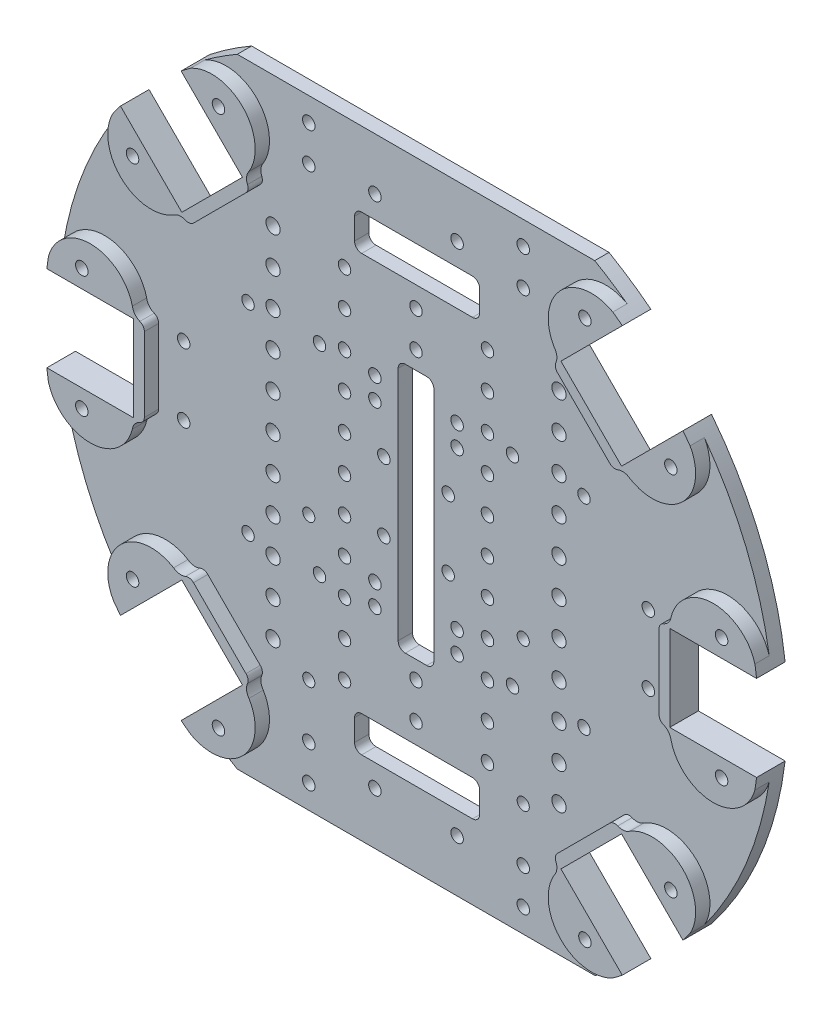
SolidWorks part; units mm, degrees
ref_plane "Front Plane" through (0, 0, 0) normal (0, 0, 1) x (1, 0, 0)
ref_plane "Top Plane" through (0, 0, 0) normal (0, 1, 0) x (1, 0, 0)
ref_plane "Right Plane" through (0, 0, 0) normal (1, 0, 0) x (0, 0, -1)
sketch "Sketch1" plane through (0, 0, 0) normal (0, 0, 1) x (1, 0, 0)
  line L0 (0, 0) -> (0, 100) construction
  line L5 (44.5477, 61.5183) -> (61.7144, 78.685)
  line L6 (44.5477, 61.5183) -> (61.5183, 44.5477)
  line L7 (-12, 75) -> (12, 75) construction
  line L8 (-12, 75) -> (-12, 99.2774) construction
  line L9 (12, 75) -> (12, 99.2774) construction
  line L10 (-17, 89.5) -> (17, 89.5) construction
  line L11 (61.5183, 44.5477) -> (78.685, 61.7144)
  line L12 (75, 12) -> (99.2774, 12)
  line L13 (75, 12) -> (75, -12)
  line L14 (75, -12) -> (99.2774, -12)
  line L15 (61.5183, -44.5477) -> (78.685, -61.7144)
  line L16 (61.5183, -44.5477) -> (44.5477, -61.5183)
  line L17 (44.5477, -61.5183) -> (61.7144, -78.685)
  line L18 (12, -75) -> (12, -99.2774) construction
  line L19 (12, -75) -> (-12, -75) construction
  line L20 (-12, -75) -> (-12, -99.2774) construction
  line L21 (-44.5477, -61.5183) -> (-61.7144, -78.685)
  line L22 (-44.5477, -61.5183) -> (-61.5183, -44.5477)
  line L23 (-61.5183, -44.5477) -> (-78.685, -61.7144)
  line L24 (-75, -12) -> (-99.2774, -12)
  line L25 (-75, -12) -> (-75, 12)
  line L26 (-75, 12) -> (-99.2774, 12)
  line L27 (-61.5183, 44.5477) -> (-78.685, 61.7144)
  line L28 (-61.5183, 44.5477) -> (-44.5477, 61.5183)
  line L29 (-44.5477, 61.5183) -> (-61.7144, 78.685)
  circle A1 centre (0, 0) radius 100
  circle A2 centre (-17, 89.5) radius 1.75 construction
  circle A3 centre (17, 89.5) radius 1.75 construction
  circle A4 centre (51.2652, 75.3069) radius 1.75
  circle A5 centre (75.3069, 51.2652) radius 1.75
  circle A6 centre (89.5, 17) radius 1.75
  circle A7 centre (89.5, -17) radius 1.75
  circle A8 centre (75.3069, -51.2652) radius 1.75
  circle A9 centre (51.2652, -75.3069) radius 1.75
  circle A10 centre (17, -89.5) radius 1.75 construction
  circle A11 centre (-17, -89.5) radius 1.75 construction
  circle A12 centre (-51.2652, -75.3069) radius 1.75
  circle A13 centre (-75.3069, -51.2652) radius 1.75
  circle A14 centre (-89.5, -17) radius 1.75
  circle A15 centre (-89.5, 17) radius 1.75
  circle A16 centre (-75.3069, 51.2652) radius 1.75
  circle A17 centre (-51.2652, 75.3069) radius 1.75
  point P2 (0, 89.5)
  point P4 (0, 75)
  point P12 (0, 75)
  point P19 (0, 89.5)
  dimension "150" = 200
  dimension "D7" = 3.5
  dimension "D2" = 25
  dimension "D3" = 8
  dimension "D4" = 24
  dimension "D5" = 14.5
  dimension "D6" = 34
extrude "Boss-Extrude1" add sketch "Sketch1" along normal blind 4 contours L12 A1 L11 L6 L5 L29 L28 L27 L26 L25 L24 L23 L22 L21 L17 L16 L15 L14 L13 A15 A14 A9 A8 A5 A4 A6 A7 A12 A13 A16 A17
sketch "Sketch2" plane through (0, 0, 4) normal (0, 0, 1) x (1, 0, 0)
  line L0 (0, 35) -> (0, -35) construction
  line L1 (-35, 35) -> (35, 35) construction
  line L2 (-35, 35) -> (-35, -35) construction
  line L3 (-35, -35) -> (35, -35) construction
  line L4 (35, 35) -> (35, -35) construction
  line L5 (-35, 35) -> (35, -35) construction
  line L6 (-35, -35) -> (35, 35) construction
  line L7 (0, 35) -> (0, 80)
  line L8 (-30, -15) -> (30, -15) construction
  line L9 (-30, -15) -> (-30, -55) construction
  line L10 (-30, -55) -> (30, -55) construction
  line L11 (30, -15) -> (30, -55) construction
  line L12 (-30, -15) -> (30, -55) construction
  line L13 (-30, -55) -> (30, -15) construction
  line L14 (-30, 80) -> (30, 80)
  line L15 (0, -55) -> (0, -80)
  line L16 (30, -80) -> (-30, -80)
  line L17 (0, 0) -> (-40, 0) construction
  line L18 (0, 0) -> (40, 0) construction
  line L19 (0, 10) -> (-40, 10)
  line L20 (0, 10) -> (40, 10)
  line L21 (0, 20) -> (-40, 20)
  line L22 (0, 20) -> (40, 20)
  line L23 (0, 30) -> (-40, 30)
  line L24 (0, 30) -> (40, 30)
  line L25 (0, 40) -> (-40, 40)
  line L26 (0, 40) -> (40, 40)
  line L27 (0, 50) -> (-40, 50)
  line L28 (0, 50) -> (40, 50)
  line L29 (0, -10) -> (40, -10)
  line L30 (0, -10) -> (-40, -10)
  line L31 (0, -20) -> (40, -20)
  line L32 (0, -20) -> (-40, -20)
  line L33 (0, -30) -> (40, -30)
  line L34 (0, -30) -> (-40, -30)
  line L35 (0, -40) -> (40, -40)
  line L36 (0, -40) -> (-40, -40)
  line L37 (0, -50) -> (40, -50)
  line L38 (0, -50) -> (-40, -50)
  line L39 (30, -70) -> (-30, -70)
  line L40 (-30, 70) -> (30, 70)
  circle A0 centre (0, 0) radius 100
  circle A1 centre (-30, -55) radius 1.7
  circle A2 centre (-30, -15) radius 1.7
  circle A3 centre (30, -55) radius 1.7
  circle A4 centre (30, -15) radius 1.7
  circle A5 centre (-30, 80) radius 1.75
  circle A6 centre (30, 80) radius 1.75
  circle A7 centre (-30, -80) radius 1.75
  circle A8 centre (30, -80) radius 1.75
  circle A9 centre (-40, 0) radius 2
  circle A10 centre (-20, 0) radius 1.75
  circle A11 centre (0, 0) radius 1.75
  circle A12 centre (40, 0) radius 2
  circle A13 centre (20, 0) radius 1.75
  circle A14 centre (20, 10) radius 1.75
  circle A15 centre (40, 10) radius 2
  circle A16 centre (-20, 10) radius 1.75
  circle A17 centre (-40, 10) radius 2
  circle A18 centre (0, 10) radius 1.75
  circle A19 centre (20, 20) radius 1.75
  circle A20 centre (40, 20) radius 2
  circle A21 centre (-20, 20) radius 1.75
  circle A22 centre (-40, 20) radius 2
  circle A23 centre (0, 20) radius 1.75
  circle A24 centre (20, 30) radius 1.75
  circle A25 centre (40, 30) radius 2
  circle A26 centre (-20, 30) radius 1.75
  circle A27 centre (-40, 30) radius 2
  circle A28 centre (0, 30) radius 1.75
  circle A29 centre (20, 40) radius 1.75
  circle A30 centre (40, 40) radius 2
  circle A31 centre (-20, 40) radius 1.75
  circle A32 centre (-40, 40) radius 2
  circle A33 centre (0, 40) radius 1.75
  circle A34 centre (20, 50) radius 1.75
  circle A35 centre (40, 50) radius 2
  circle A36 centre (-20, 50) radius 1.75
  circle A37 centre (-40, 50) radius 2
  circle A38 centre (0, 50) radius 1.75
  circle A39 centre (40, -10) radius 2
  circle A40 centre (0, -10) radius 1.75
  circle A41 centre (20, -10) radius 1.75
  circle A42 centre (-20, -10) radius 1.75
  circle A43 centre (-40, -10) radius 2
  circle A44 centre (40, -20) radius 2
  circle A45 centre (0, -20) radius 1.75
  circle A46 centre (20, -20) radius 1.75
  circle A47 centre (-20, -20) radius 1.75
  circle A48 centre (-40, -20) radius 2
  circle A49 centre (40, -30) radius 2
  circle A50 centre (0, -30) radius 1.75
  circle A51 centre (20, -30) radius 1.75
  circle A52 centre (-20, -30) radius 1.75
  circle A53 centre (-40, -30) radius 2
  circle A54 centre (40, -40) radius 2
  circle A55 centre (0, -40) radius 1.75
  circle A56 centre (20, -40) radius 1.75
  circle A57 centre (-20, -40) radius 1.75
  circle A58 centre (-40, -40) radius 2
  circle A59 centre (40, -50) radius 2
  circle A60 centre (0, -50) radius 1.75
  circle A61 centre (20, -50) radius 1.75
  circle A62 centre (-20, -50) radius 1.75
  circle A63 centre (-40, -50) radius 2
  circle A64 centre (30, -70) radius 1.75
  circle A65 centre (-30, -70) radius 1.75
  circle A66 centre (-30, 70) radius 1.75
  circle A67 centre (30, 70) radius 1.75
  point P10 (0, 0)
  point P23 (0, 80)
  point P30 (0, -80)
  dimension "D1" = 200
  dimension "D6" = 3.4
  dimension "D9" = 3.5
  dimension "D10" = 3.5
  dimension "D13" = 3.5
  dimension "D14" = 3.5
  dimension "D16" = 4
  dimension "D17" = 3.5
  dimension "D18" = 3.5
  dimension "D2" = 70
  dimension "D3" = 70
  dimension "D4" = 40
  dimension "D5" = 60
  dimension "D7" = 45
  dimension "D8" = 60
  dimension "D11" = 25
  dimension "D12" = 60
  dimension "D15" = 40
  dimension "D19" = 6
  dimension "D20" = 6
  dimension "D21" = 2
  dimension "D22" = 2
extrude "Cut-Extrude1" cut sketch "Sketch2" against normal blind 10
sketch "Sketch3" plane through (0, 0, 4) normal (0, 0, 1) x (1, 0, 0)
  line L0 (-78.685, 61.7144) -> (-61.5183, 44.5477)
  line L1 (-61.5183, 44.5477) -> (-44.5477, 61.5183)
  line L2 (-44.5477, 61.5183) -> (-61.7144, 78.685)
  line L3 (-58.255, 43.5684) -> (-43.5684, 58.255)
  line L4 (-53.033, 53.033) -> (-50.9117, 50.9117)
  line L5 (-10.385, 72) -> (10.385, 72)
  line L6 (-12, 75) -> (12, 75)
  line L7 (-12, 99.2774) -> (-12, 75)
  line L8 (12, 75) -> (12, 99.2774)
  line L9 (43.5684, 58.255) -> (58.255, 43.5684)
  line L10 (44.5477, 61.5183) -> (61.5183, 44.5477)
  line L11 (61.7144, 78.685) -> (44.5477, 61.5183)
  line L12 (61.5183, 44.5477) -> (78.685, 61.7144)
  line L13 (72, 10.385) -> (72, -10.385)
  line L14 (75, 12) -> (75, -12)
  line L15 (99.2774, 12) -> (75, 12)
  line L16 (75, -12) -> (99.2774, -12)
  line L17 (58.255, -43.5684) -> (43.5684, -58.255)
  line L18 (61.5183, -44.5477) -> (44.5477, -61.5183)
  line L19 (78.685, -61.7144) -> (61.5183, -44.5477)
  line L20 (44.5477, -61.5183) -> (61.7144, -78.685)
  line L21 (10.385, -72) -> (-10.385, -72)
  line L22 (12, -75) -> (-12, -75)
  line L23 (12, -99.2774) -> (12, -75)
  line L24 (-12, -75) -> (-12, -99.2774)
  line L25 (-43.5684, -58.255) -> (-58.255, -43.5684)
  line L26 (-44.5477, -61.5183) -> (-61.5183, -44.5477)
  line L27 (-61.7144, -78.685) -> (-44.5477, -61.5183)
  line L28 (-61.5183, -44.5477) -> (-78.685, -61.7144)
  line L29 (-72, -10.385) -> (-72, 10.385)
  line L30 (-75, -12) -> (-75, 12)
  line L31 (-99.2774, -12) -> (-75, -12)
  line L32 (-75, 12) -> (-99.2774, 12)
  arc A1 (-12.2421, 73.2574) -> (-10.385, 72) centre (-10.385, 74) ccw
  circle A2 centre (0, 0) radius 100
  arc A3 (-61.5183, 44.5477) -> (-78.685, 61.7144) centre (-70.1016, 53.1311) cw
  arc A4 (-61.7144, 78.685) -> (-44.5477, 61.5183) centre (-53.1311, 70.1016) cw
  circle A5 centre (-51.2652, 75.3069) radius 1.75
  circle A6 centre (-75.3069, 51.2652) radius 1.75
  arc A7 (-43.1444, 60.4573) -> (-42.7452, 63.8182) centre (-40.0316, 61.7918) cw
  arc A8 (-60.4573, 43.1444) -> (-63.8182, 42.7452) centre (-61.7918, 40.0316) ccw
  arc A9 (-60.4573, 43.1444) -> (-58.255, 43.5684) centre (-59.6692, 44.9826) ccw
  arc A10 (-43.1444, 60.4573) -> (-43.5684, 58.255) centre (-44.9826, 59.6692) cw
  arc A11 (-12.2421, 73.2574) -> (-14.9009, 75.3517) centre (-15.3867, 72) ccw
  arc A12 (-12, 75) -> (-12, 99.2774) centre (-12, 87.1387) cw
  circle A13 centre (-17, 89.5) radius 1.75
  circle A14 centre (17, 89.5) radius 1.75
  arc A15 (12, 99.2774) -> (12, 75) centre (12, 87.1387) cw
  arc A16 (12.2421, 73.2574) -> (14.9009, 75.3517) centre (15.3867, 72) cw
  arc A17 (12.2421, 73.2574) -> (10.385, 72) centre (10.385, 74) cw
  arc A18 (43.1444, 60.4573) -> (43.5684, 58.255) centre (44.9826, 59.6692) ccw
  arc A19 (43.1444, 60.4573) -> (42.7452, 63.8182) centre (40.0316, 61.7918) ccw
  arc A20 (44.5477, 61.5183) -> (61.7144, 78.685) centre (53.1311, 70.1016) cw
  circle A21 centre (51.2652, 75.3069) radius 1.75
  circle A22 centre (75.3069, 51.2652) radius 1.75
  arc A23 (78.685, 61.7144) -> (61.5183, 44.5477) centre (70.1016, 53.1311) cw
  arc A24 (60.4573, 43.1444) -> (63.8182, 42.7452) centre (61.7918, 40.0316) cw
  arc A25 (60.4573, 43.1444) -> (58.255, 43.5684) centre (59.6692, 44.9826) cw
  arc A26 (73.2574, 12.2421) -> (72, 10.385) centre (74, 10.385) ccw
  arc A27 (73.2574, 12.2421) -> (75.3517, 14.9009) centre (72, 15.3867) ccw
  arc A28 (75, 12) -> (99.2774, 12) centre (87.1387, 12) cw
  circle A29 centre (89.5, 17) radius 1.75
  circle A30 centre (89.5, -17) radius 1.75
  arc A31 (99.2774, -12) -> (75, -12) centre (87.1387, -12) cw
  arc A32 (73.2574, -12.2421) -> (75.3517, -14.9009) centre (72, -15.3867) cw
  arc A33 (73.2574, -12.2421) -> (72, -10.385) centre (74, -10.385) cw
  arc A34 (60.4573, -43.1444) -> (58.255, -43.5684) centre (59.6692, -44.9826) ccw
  arc A35 (60.4573, -43.1444) -> (63.8182, -42.7452) centre (61.7918, -40.0316) ccw
  arc A36 (61.5183, -44.5477) -> (78.685, -61.7144) centre (70.1016, -53.1311) cw
  circle A37 centre (75.3069, -51.2652) radius 1.75
  circle A38 centre (51.2652, -75.3069) radius 1.75
  arc A39 (61.7144, -78.685) -> (44.5477, -61.5183) centre (53.1311, -70.1016) cw
  arc A40 (43.1444, -60.4573) -> (42.7452, -63.8182) centre (40.0316, -61.7918) cw
  arc A41 (43.1444, -60.4573) -> (43.5684, -58.255) centre (44.9826, -59.6692) cw
  arc A42 (12.2421, -73.2574) -> (10.385, -72) centre (10.385, -74) ccw
  arc A43 (12.2421, -73.2574) -> (14.9009, -75.3517) centre (15.3867, -72) ccw
  arc A44 (12, -75) -> (12, -99.2774) centre (12, -87.1387) cw
  circle A45 centre (17, -89.5) radius 1.75
  circle A46 centre (-17, -89.5) radius 1.75
  arc A47 (-12, -99.2774) -> (-12, -75) centre (-12, -87.1387) cw
  arc A48 (-12.2421, -73.2574) -> (-14.9009, -75.3517) centre (-15.3867, -72) cw
  arc A49 (-12.2421, -73.2574) -> (-10.385, -72) centre (-10.385, -74) cw
  arc A50 (-43.1444, -60.4573) -> (-43.5684, -58.255) centre (-44.9826, -59.6692) ccw
  arc A51 (-43.1444, -60.4573) -> (-42.7452, -63.8182) centre (-40.0316, -61.7918) ccw
  arc A52 (-44.5477, -61.5183) -> (-61.7144, -78.685) centre (-53.1311, -70.1016) cw
  circle A53 centre (-51.2652, -75.3069) radius 1.75
  circle A54 centre (-75.3069, -51.2652) radius 1.75
  arc A55 (-78.685, -61.7144) -> (-61.5183, -44.5477) centre (-70.1016, -53.1311) cw
  arc A56 (-60.4573, -43.1444) -> (-63.8182, -42.7452) centre (-61.7918, -40.0316) cw
  arc A57 (-60.4573, -43.1444) -> (-58.255, -43.5684) centre (-59.6692, -44.9826) cw
  arc A58 (-73.2574, -12.2421) -> (-72, -10.385) centre (-74, -10.385) ccw
  arc A59 (-73.2574, -12.2421) -> (-75.3517, -14.9009) centre (-72, -15.3867) ccw
  arc A60 (-75, -12) -> (-99.2774, -12) centre (-87.1387, -12) cw
  circle A61 centre (-89.5, -17) radius 1.75
  circle A62 centre (-89.5, 17) radius 1.75
  arc A63 (-99.2774, 12) -> (-75, 12) centre (-87.1387, 12) cw
  arc A64 (-73.2574, 12.2421) -> (-75.3517, 14.9009) centre (-72, 15.3867) cw
  arc A65 (-73.2574, 12.2421) -> (-72, 10.385) centre (-74, 10.385) cw
  point P29 (-59.397, 42.4264)
  point P32 (-42.4264, 59.397)
  dimension "D2" = 2
  dimension "D1" = 2
  dimension "D3" = 8
extrude "Boss-Extrude2" add sketch "Sketch3" along normal blind 4 contours A39 A40 A2 L20 A38 | A41 A40 A39 L18 A36 A35 A34 L17 | A36 L19 A2 A35 A37 | A31 A32 A2 L16 A30 | A33 A32 A31 L14 A28 A27 A26 L13 | A28 L15 A2 A27 A29 | A23 A24 A2 L12 A22 | A25 A24 A23 L10 A20 A19 A18 L9 | A20 L11 A2 A19 A21 | A4 A7 A2 L2 A5 | A10 A7 A4 L1 L4 L3 | A8 A9 L3 L4 L1 A3 | A8 A3 L0 A2 A6 | A63 A64 A2 L32 A62 | A65 A64 A63 L30 A60 A59 A58 L29 | A60 L31 A2 A59 A61 | A55 A56 A2 L28 A54 | A57 A56 A55 L26 A52 A51 A50 L25 | A52 L27 A2 A51 A53
sketch "Sketch4" plane through (0, 0, 0) normal (0, 0, -1) x (-1, 0, 0)
  line L0 (-11.5, 72) -> (-11.5, 28)
  line L1 (-11.5, 22) -> (11.5, 22) construction
  line L2 (-11.5, 22) -> (-11.5, -22) construction
  line L3 (-11.5, -22) -> (11.5, -22) construction
  line L4 (11.5, 22) -> (11.5, -22) construction
  line L5 (-11.5, 22) -> (11.5, -22) construction
  line L6 (-11.5, -22) -> (11.5, 22) construction
  line L7 (-11.5, 72) -> (11.5, 72)
  line L8 (11.5, 72) -> (11.5, 28)
  line L9 (-11.5, 28) -> (11.5, 28)
  line L10 (-11.5, 22) -> (-11.5, -22)
  line L11 (-11.5, 22) -> (11.5, 22)
  line L12 (11.5, 22) -> (11.5, -22)
  line L13 (-11.5, -22) -> (11.5, -22)
  line L14 (-11.5, -28) -> (-11.5, -72)
  line L15 (-11.5, -28) -> (11.5, -28)
  line L16 (11.5, -28) -> (11.5, -72)
  line L17 (-11.5, -72) -> (11.5, -72)
  line L18 (0, 0) -> (100, 0)
  line L19 (-47, 28) -> (-47, -28)
  line L20 (35, 28) -> (55, 28) construction
  line L21 (35, 28) -> (35, -28) construction
  line L22 (35, -28) -> (55, -28) construction
  line L23 (55, 28) -> (55, -28) construction
  line L24 (35, 28) -> (55, -28) construction
  line L25 (35, -28) -> (55, 28) construction
  line L26 (-47, 28) -> (-27, 28)
  line L27 (-27, 28) -> (-27, -28)
  line L28 (-47, -28) -> (-27, -28)
  line L29 (0, 22) -> (0, -22)
  line L30 (47, 28) -> (27, 28)
  line L31 (27, 28) -> (27, -28)
  line L32 (47, -28) -> (27, -28)
  line L33 (47, 28) -> (47, -28)
  circle A0 centre (0, 0) radius 100
  circle A1 centre (-11.5, 22) radius 1.75
  circle A2 centre (11.5, 22) radius 1.75
  circle A3 centre (11.5, -22) radius 1.75
  circle A4 centre (-11.5, -22) radius 1.75
  circle A5 centre (11.5, 72) radius 1.75
  circle A6 centre (-11.5, 72) radius 1.75
  circle A7 centre (-11.5, 28) radius 1.75
  circle A8 centre (11.5, 28) radius 1.75
  circle A9 centre (11.5, 22) radius 1.75
  circle A10 centre (-11.5, 22) radius 1.75
  circle A11 centre (-11.5, -22) radius 1.75
  circle A12 centre (11.5, -22) radius 1.75
  circle A13 centre (11.5, -28) radius 1.75
  circle A14 centre (-11.5, -28) radius 1.75
  circle A15 centre (-11.5, -72) radius 1.75
  circle A16 centre (11.5, -72) radius 1.75
  circle A17 centre (35, 28) radius 1.75 construction
  circle A18 centre (55, 28) radius 1.75 construction
  circle A19 centre (55, -28) radius 1.75 construction
  circle A20 centre (35, -28) radius 1.75 construction
  circle A21 centre (-47, 28) radius 1.75
  circle A22 centre (-27, 28) radius 1.75
  circle A23 centre (-47, -28) radius 1.75
  circle A24 centre (-27, -28) radius 1.75
  circle A25 centre (47, 28) radius 1.75
  circle A26 centre (27, 28) radius 1.75
  circle A27 centre (47, -28) radius 1.75
  circle A28 centre (27, -28) radius 1.75
  point P11 (45, 0)
  point P13 (45, 0)
  dimension "D3" = 3.5
  dimension "D9" = 3.5
  dimension "D1" = 44
  dimension "D2" = 23
  dimension "D6" = 45
  dimension "D7" = 56
  dimension "D8" = 20
  dimension "D4" = 2
  dimension "D5" = 2
  dimension "D10" = 2
extrude "Cut-Extrude2" cut sketch "Sketch4" against normal blind 10 contours L8 A5 L7 | L7 A5 L8 | L7 A6 L0 | L0 A6 L7 | L0 A7 L9 | L9 A7 L0 | L9 A8 L8 | L8 A8 L9 | L12 A2 L11 | L11 A2 L12 | L11 A1 L10 | L10 A1 L11 | L12 A3 L13 | L13 A3 L12 | L13 A4 L10 | L10 A4 L13 | L15 A14 L14 | L14 A14 L15 | L15 A13 L16 | L16 A13 L15 | L14 A15 L17 | L17 A15 L14 | L17 A16 L16 | L16 A16 L17 | L26 A21 L19 | L19 A21 L26 | L26 A22 L27 | L27 A22 L26 | L28 A24 L27 | L27 A24 L28 | L19 A23 L28 | L28 A23 L19 | A25 L30 L33 | A25 L33 L30 | A26 L30 L31 | A26 L31 L30 | A27 L33 L32 | A27 L32 L33 | A28 L32 L31 | A28 L31 L32
sketch "Sketch5" plane through (0, 0, 0) normal (0, 0, -1) x (-1, 0, 0)
  line L0 (9, 9.6) -> (9, -9.6) construction
  line L1 (-3, 35) -> (3, 35)
  line L2 (-5, 33) -> (-5, -33)
  line L3 (-3, -35) -> (3, -35)
  line L4 (5, 33) -> (5, -33)
  line L5 (-5, 35) -> (5, -35) construction
  line L6 (-5, -35) -> (5, 35) construction
  line L7 (-28, 9.6) -> (28, 9.6) construction
  line L8 (-28, 9.6) -> (-28, -9.6) construction
  line L9 (-28, -9.6) -> (28, -9.6) construction
  line L10 (28, 9.6) -> (28, -9.6) construction
  line L11 (-28, 9.6) -> (28, -9.6) construction
  line L12 (-28, -9.6) -> (28, 9.6) construction
  line L13 (9, 9.6) -> (65, 9.6) construction
  line L14 (65, 9.6) -> (65, -9.6) construction
  line L15 (9, -9.6) -> (65, -9.6) construction
  line L16 (0, 35) -> (0, 0) construction
  line L17 (0, 0) -> (5, 0) construction
  line L18 (-15.8022, -55.7522) -> (15.1978, -55.7522)
  line L19 (-17.8022, -57.7522) -> (-17.8022, -63.7522)
  line L20 (-15.8022, -65.7522) -> (15.1978, -65.7522)
  line L21 (17.1978, -57.7522) -> (17.1978, -63.7522)
  line L22 (-17.8022, -55.7522) -> (17.1978, -65.7522) construction
  line L23 (-17.8022, -65.7522) -> (17.1978, -55.7522) construction
  line L24 (-15.8022, 65.7522) -> (15.1978, 65.7522)
  line L25 (17.1978, 57.7522) -> (17.1978, 63.7522)
  line L26 (-15.8022, 55.7522) -> (15.1978, 55.7522)
  line L27 (-17.8022, 57.7522) -> (-17.8022, 63.7522)
  circle A0 centre (0, 0) radius 100
  arc A1 (17.1978, -57.7522) -> (15.1978, -55.7522) centre (15.1978, -57.7522) ccw
  arc A2 (3, -35) -> (5, -33) centre (3, -33) ccw
  arc A3 (-3, -35) -> (-5, -33) centre (-3, -33) cw
  arc A4 (3, 35) -> (5, 33) centre (3, 33) cw
  arc A5 (-3, 35) -> (-5, 33) centre (-3, 33) ccw
  circle A6 centre (-28, 9.6) radius 1.75 construction
  circle A7 centre (-28, -9.6) radius 1.75 construction
  circle A8 centre (28, 9.6) radius 1.75 construction
  circle A9 centre (28, -9.6) radius 1.75 construction
  circle A10 centre (9, 9.6) radius 1.75
  circle A11 centre (9, -9.6) radius 1.75
  circle A12 centre (65, 9.6) radius 1.75
  circle A13 centre (65, -9.6) radius 1.75
  circle A14 centre (-9, 9.6) radius 1.75
  circle A15 centre (-9, -9.6) radius 1.75
  circle A16 centre (-65, -9.6) radius 1.75
  circle A17 centre (-65, 9.6) radius 1.75
  arc A18 (17.1978, -63.7522) -> (15.1978, -65.7522) centre (15.1978, -63.7522) cw
  arc A19 (-17.8022, -63.7522) -> (-15.8022, -65.7522) centre (-15.8022, -63.7522) ccw
  arc A20 (-15.8022, -55.7522) -> (-17.8022, -57.7522) centre (-15.8022, -57.7522) ccw
  arc A21 (17.1978, 63.7522) -> (15.1978, 65.7522) centre (15.1978, 63.7522) ccw
  arc A22 (17.1978, 57.7522) -> (15.1978, 55.7522) centre (15.1978, 57.7522) cw
  arc A23 (-17.8022, 63.7522) -> (-15.8022, 65.7522) centre (-15.8022, 63.7522) cw
  arc A24 (-15.8022, 55.7522) -> (-17.8022, 57.7522) centre (-15.8022, 57.7522) cw
  point P44 (-0.3022, -60.7522)
  dimension "D3" = 2
  dimension "D6" = 3.5
  dimension "D10" = 2
  dimension "D1" = 70
  dimension "D2" = 10
  dimension "D4" = 19.2
  dimension "D5" = 56
  dimension "D8" = 10
  dimension "D9" = 35
  dimension "D7" = 2
extrude "Cut-Extrude4" cut sketch "Sketch5" against normal blind 10 contours A5 L1 A4 L4 A2 L3 A3 L2 | A14 | A10 | A11 | A15 | A17 | A16 | A12 | A13 | L19 A19 L20 A18 L21 A1 L18 A20 | L24 A21 L25 A22 L26 A24 L27 A23
sketch "Sketch6" plane through (0, 0, 4) normal (0, 0, 1) x (1, 0, 0)
  line L0 (0, 0) -> (0, -100) construction
  line L1 (-50, -86.6025) -> (50, -86.6025)
  line L2 (0, 0) -> (-100, 0) construction
  line L4 (-50, 86.6025) -> (50, 86.6025)
  circle A0 centre (0, 0) radius 100
  point P7 (0, -86.6025)
  dimension "D1" = 200
  dimension "D2" = 100
extrude "Cut-Extrude6" cut sketch "Sketch6" against normal blind 10 contours L4 A0 | L1 A0
sketch "Sketch7" plane through (8.4853, 8.4853, 0) normal (-0.7071, -0.7071, 0) x (0, 0, 1)
  line L1 (8, 99.2774) -> (0, 99.2774)
  line L2 (8, 99.2774) -> (8, 75)
  line L3 (8, 75) -> (0, 75)
  line L4 (0, 99.2774) -> (0, 75)
  line L5 (2.854, 93.5395) -> (8.0043, 93.5395)
  line L6 (2.854, 93.5395) -> (2.854, 84.9449)
  line L7 (2.854, 84.9449) -> (8.0043, 84.9449)
  line L8 (8.0043, 93.5395) -> (8.0043, 84.9449)
  dimension "D1" = 5.146
